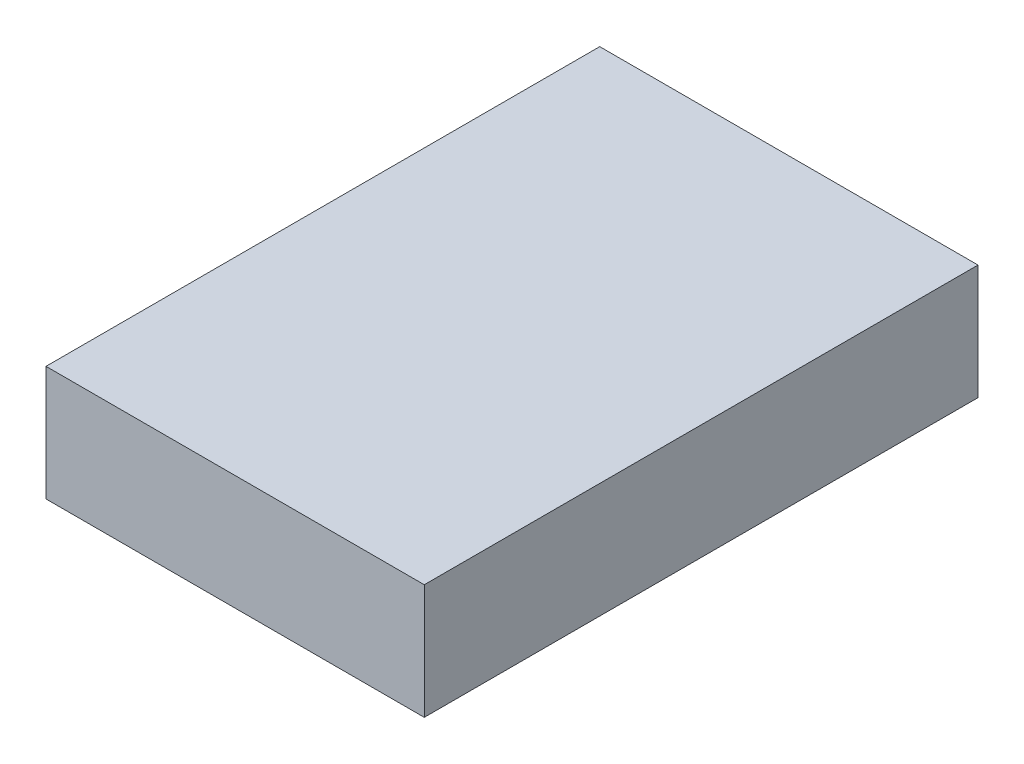
SolidWorks part; units mm, degrees
other "Markup1"
sketch "Sketch3" plane through (50.8, 12.7, 0) normal (0.5774, 0.5773, 0.5774) x (0.7071, 0, -0.7071)
material "Oak"
ref_plane "Front Plane" through (0, 0, 0) normal (0, 0, 1) x (1, 0, 0)
ref_plane "Top Plane" through (0, 0, 0) normal (0, 1, 0) x (1, 0, 0)
ref_plane "Right Plane" through (0, 0, 0) normal (1, 0, 0) x (0, 0, -1)
sketch "Sketch2" plane through (0, 0, 0) normal (0, 1, 0) x (1, 0, 0)
  line L0 (0, 0) -> (21.4122, 0)
  line L1 (21.4122, 0) -> (21.4122, 31.3436)
  line L2 (21.4122, 31.3436) -> (0, 31.3436)
  line L3 (0, 31.3436) -> (0, 0)
  dimension "D1" = 31.3436
  dimension "D2" = 21.4122
extrude "Boss-Extrude1" add sketch "Sketch2" along normal blind 6.5024
